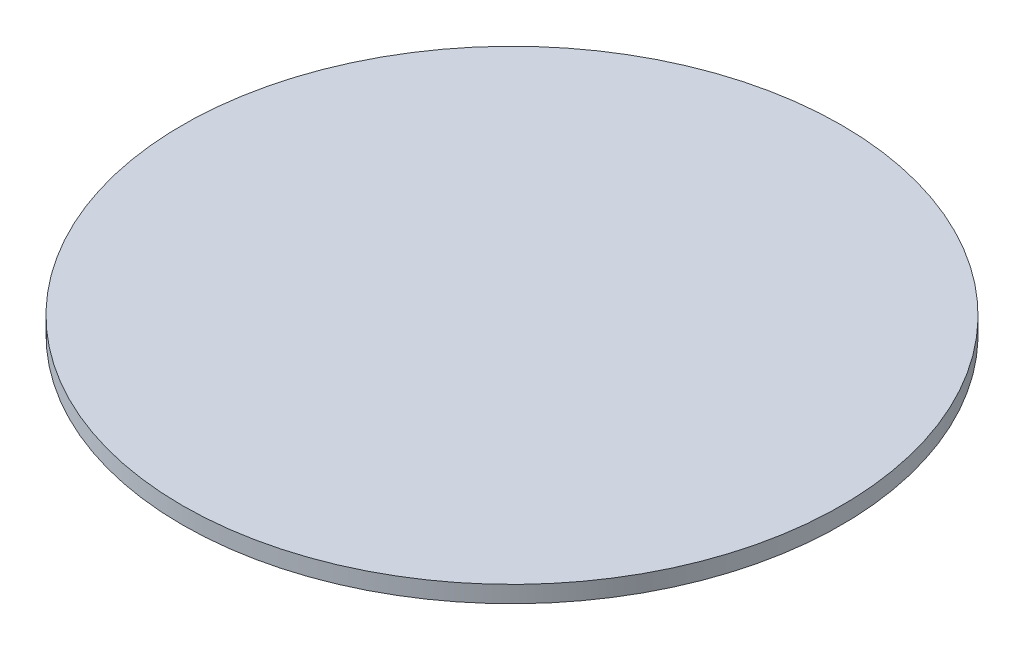
SolidWorks part; units mm, degrees
ref_plane "Front" through (0, 0, 0) normal (0, 0, 1) x (1, 0, 0)
ref_plane "Top" through (0, 0, 0) normal (0, 1, 0) x (1, 0, 0)
ref_plane "Right" through (0, 0, 0) normal (1, 0, 0) x (0, 0, -1)
sketch "Sketch2" plane through (0, 0, 0) normal (0, 1, 0) x (1, 0, 0)
  circle A0 centre (0, 0) radius 59
  dimension "D1" = 118
extrude "Boss-Extrude1" add sketch "Sketch2" along normal blind 3
